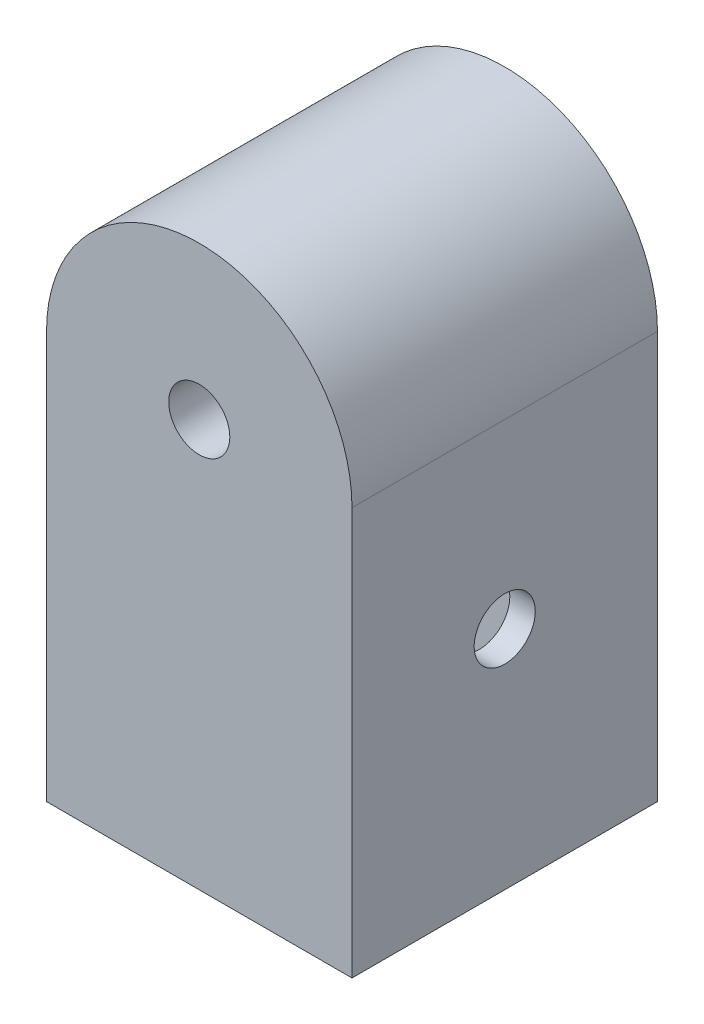
SolidWorks part; units mm, degrees
ref_plane "Front Plane" through (0, 0, 0) normal (0, 0, 1) x (1, 0, 0)
ref_plane "Top Plane" through (0, 0, 0) normal (0, 1, 0) x (1, 0, 0)
ref_plane "Right Plane" through (0, 0, 0) normal (1, 0, 0) x (0, 0, -1)
sketch "Sketch1" plane through (0, 0, 0) normal (0, 1, 0) x (1, 0, 0)
  line L1 (-7.5, 7.5) -> (7.5, 7.5)
  line L2 (-7.5, 7.5) -> (-7.5, -7.5)
  line L3 (-7.5, -7.5) -> (7.5, -7.5)
  line L4 (7.5, 7.5) -> (7.5, -7.5)
  line L5 (-7.5, 7.5) -> (7.5, -7.5) construction
  line L6 (-7.5, -7.5) -> (7.5, 7.5) construction
  point P0 (0, 0)
  dimension "D1" = 15
  dimension "D2" = 15
extrude "Boss-Extrude1" add sketch "Sketch1" along normal blind 20
sketch "Sketch2" plane through (0, 20, 0) normal (0, 1, 0) x (1, 0, 0)
  line L1 (-6.25, 6.25) -> (6.25, 6.25)
  line L2 (-6.25, 6.25) -> (-6.25, -6.25)
  line L3 (-6.25, -6.25) -> (6.25, -6.25)
  line L4 (6.25, 6.25) -> (6.25, -6.25)
  line L5 (-6.25, 6.25) -> (6.25, -6.25) construction
  line L6 (-6.25, -6.25) -> (6.25, 6.25) construction
  point P0 (0, 0)
  dimension "D1" = 12.5
  dimension "D2" = 12.5
extrude "Cut-Extrude1" cut sketch "Sketch2" against normal up to surface (17 mm away) from offset 3 up to face at (0, 0, 0) offset against normal yes
sketch "Sketch5" plane through (0, 0, -7.5) normal (0, 0, -1) x (-1, 0, 0)
  line L0 (-7.5, 20) -> (7.5, 20)
  arc A0 (7.5, 20) -> (-7.5, 20) centre (0, 20) ccw
  dimension "D1" = 7.5
extrude "Boss-Extrude3" add sketch "Sketch5" against normal through all
sketch "Sketch6" plane through (7.5, 0, 0) normal (1, 0, 0) x (0, 0, -1)
  circle A0 centre (0, 11.0969) radius 1.5
  dimension "D1" = 3
extrude "Cut-Extrude2" cut sketch "Sketch6" against normal through all
sketch "Sketch7" plane through (0, 0, 7.5) normal (0, 0, 1) x (1, 0, 0)
  circle A0 centre (0, 20) radius 1.5
  dimension "D1" = 3
extrude "Cut-Extrude3" cut sketch "Sketch7" against normal through all
